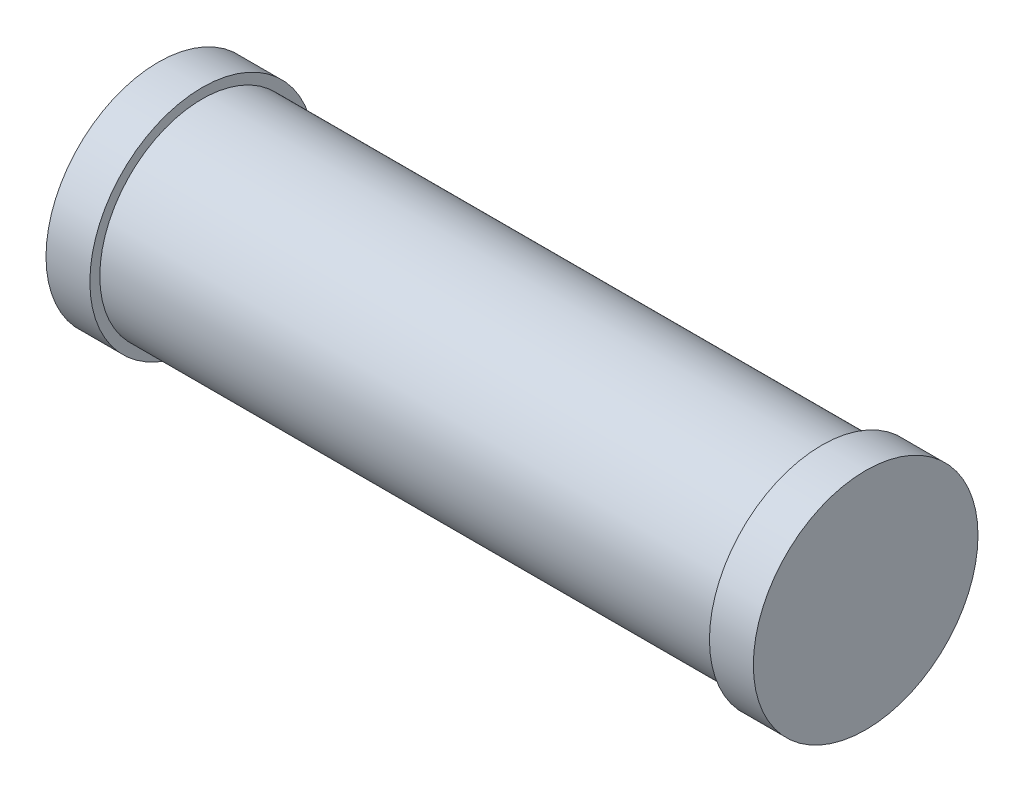
SolidWorks part; units mm, degrees
ref_plane "Front Plane" through (0, 0, 0) normal (0, 0, 1) x (1, 0, 0)
ref_plane "Top Plane" through (0, 0, 0) normal (0, 1, 0) x (1, 0, 0)
ref_plane "Right Plane" through (0, 0, 0) normal (1, 0, 0) x (0, 0, -1)
sketch "Sketch2" plane through (0, 0, 0) normal (0, 1, 0) x (1, 0, 0)
  line L0 (79.2012, 0) -> (0, 0) construction
  line L1 (0, 0) -> (-62.3416, 0) construction
  line L2 (-17.65, 5.835) -> (17.65, 5.835)
  line L3 (17.65, 5.835) -> (17.65, 6.4)
  line L4 (17.65, 6.4) -> (20.15, 6.4)
  line L5 (20.15, 6.4) -> (20.15, 0)
  line L6 (0, 0) -> (0, 5.835) construction
  line L7 (-20.15, 6.4) -> (-20.15, 0)
  line L8 (-17.65, 6.4) -> (-20.15, 6.4)
  line L9 (-17.65, 5.835) -> (-17.65, 6.4)
  line L10 (20.15, 0) -> (-20.15, 0)
  dimension "D1" = 5.835
  dimension "D2" = 6.4
  dimension "D3" = 17.65
  dimension "D4" = 2.5
revolve "Revolve1" add sketch "Sketch2" angle 360 about L10
ref_plane "Plane1" through (12.7, 0, 0) normal (1, 0, 0) x (0, 0, -1)
